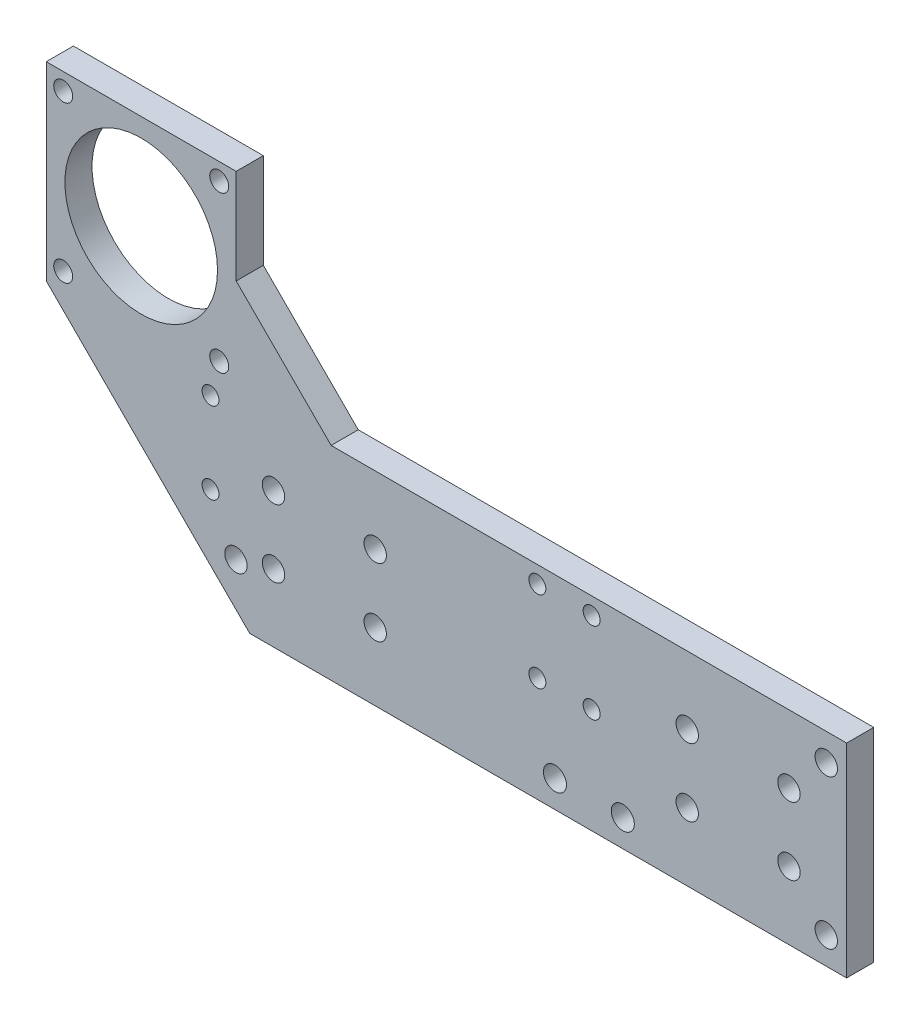
SolidWorks part; units mm, degrees
ref_plane "前视基准面" through (0, 0, 0) normal (0, 0, 1) x (1, 0, 0)
ref_plane "上视基准面" through (0, 0, 0) normal (0, 1, 0) x (1, 0, 0)
ref_plane "右视基准面" through (0, 0, 0) normal (1, 0, 0) x (0, 0, -1)
other "Configuration Table"
sketch "草图1" plane through (0, 0, 0) normal (0, 0, 1) x (1, 0, 0)
  line L1 (-56, -29) -> (56, -29)
  line L2 (-56, -29) -> (-56, 29)
  line L3 (-56, 29) -> (56, 29)
  line L4 (56, -29) -> (56, 29)
  line L5 (-56, -29) -> (56, 29) construction
  line L6 (-56, 29) -> (56, -29) construction
  point P0 (0, 0)
  dimension "D1" = 112
  dimension "D2" = 58
extrude "凸台-拉伸1" add sketch "草图1" along normal blind 4
sketch "草图2" plane through (0, 0, 4) normal (0, 0, 1) x (1, 0, 0)
  line L0 (56, 1) -> (-14, 1)
  line L1 (56, -29) -> (56, 29) construction
  line L3 (56, 29) -> (-56, 29) construction
  line L4 (-28, 29) -> (-56, 29)
  line L5 (-56, 29) -> (-56, 1)
  line L6 (-56, 29) -> (-56, -29) construction
  line L7 (-56, 1) -> (-26, -29)
  line L8 (-56, -29) -> (56, -29) construction
  line L9 (-26, -29) -> (56, -29)
  line L10 (56, -29) -> (56, 1)
  line L11 (-28, 29) -> (-28, 15)
  line L12 (-14, 1) -> (-28, 15)
  dimension "D1" = 45
extrude "切除-拉伸1" cut sketch "草图2" against normal blind 4 flip side to cut
sketch "草图3" plane through (0, 0, 4) normal (0, 0, 1) x (1, 0, 0)
  circle A0 centre (-42, 15) radius 11.25
  dimension "D1" = 22.5
extrude "切除-拉伸2" cut sketch "草图3" against normal blind 4
sketch "草图4" plane through (0, 0, 4) normal (0, 0, 1) x (1, 0, 0)
  circle A0 centre (-22.5, -19) radius 1.65
  circle A1 centre (-22.5, -9) radius 1.65
  circle A2 centre (-7.5, -19) radius 1.65
  circle A3 centre (-7.5, -9) radius 1.65
  circle A4 centre (38.5, -19) radius 1.65
  circle A5 centre (38.5, -9) radius 1.65
  circle A6 centre (53.5, -19) radius 1.65
  circle A7 centre (53.5, -9) radius 1.65
  circle A10 centre (19, -25) radius 1.7
  circle A11 centre (29, -25) radius 1.7
  dimension "D1" = 3.3
  dimension "D2" = 3.4
extrude "切除-拉伸3" cut sketch "草图4" against normal up to next
sketch "草图5" plane through (0, 0, 0) normal (0, 0, -1) x (-1, 0, 0)
  circle A0 centre (-16.406, -13.5) radius 1.25
  circle A1 centre (-24.406, -13.5) radius 1.25
  circle A2 centre (-16.406, -1.5) radius 1.25
  circle A3 centre (-24.406, -1.5) radius 1.25
  circle A4 centre (31.7799, -13.5) radius 1.25
  circle A5 centre (31.7799, -1.5) radius 1.25
  point P12 (-25.6794, -13.5)
  point P13 (-16.8753, -13.5)
  point P14 (-24.8754, -1.5)
  point P15 (-16.8753, -1.5)
  dimension "D1" = 2.5
extrude "切除-拉伸4" cut sketch "草图5" against normal up to next
sketch "草图6" plane through (56, 0, 0) normal (1, 0, 0) x (0, 0, -1)
  line L0 (0, -29) -> (0, 1) construction
  line L1 (0, -29) -> (-4, -29)
  line L2 (0, -29) -> (0, 1)
  line L3 (0, 1) -> (-4, 1)
  line L4 (-4, -29) -> (-4, 1)
  line L5 (-4, 1) -> (-4, 15) construction
sketch "草图8" plane through (0, 0, 0) normal (0, 0, -1) x (-1, 0, 0)
  line L0 (-56, -29) -> (-56, 1) construction
  line L1 (-56, 1) -> (-62, 1)
  line L2 (-56, 1) -> (-56, -29)
  line L3 (-56, -29) -> (-62, -29)
  line L4 (-62, 1) -> (-62, -29)
  dimension "D1" = 6
extrude "凸台-拉伸3" add sketch "草图8" against normal blind 4
sketch "草图10" plane through (0, 0, 4) normal (0, 0, 1) x (1, 0, 0)
  line L1 (62, 1) -> (62, -29) construction
  line L2 (-26, -29) -> (62, -29) construction
  line L3 (62, 1) -> (-14, 1) construction
  circle A0 centre (59, -25) radius 1.65
  circle A1 centre (59, -3) radius 1.65
  dimension "D1" = 3.3
  dimension "D2" = 3.3
  dimension "D3" = 3
  dimension "D4" = 3
  dimension "D5" = 4
  dimension "D6" = 4
extrude "切除-拉伸5" cut sketch "草图10" against normal up to next
sketch "草图11" plane through (0, 0, 4) normal (0, 0, 1) x (1, 0, 0)
  circle A0 centre (-28.0366, -20.5937) radius 1.65
  dimension "D1" = 3.3
extrude "切除-拉伸6" cut sketch "草图11" against normal up to next
sketch "草图13" plane through (0, 0, 0) normal (0, 0, -1) x (-1, 0, 0)
  line L1 (30.5, 26.5) -> (53.5, 26.5) construction
  line L2 (30.5, 26.5) -> (30.5, 3.5) construction
  line L3 (30.5, 3.5) -> (53.5, 3.5) construction
  line L4 (53.5, 26.5) -> (53.5, 3.5) construction
  line L5 (30.5, 26.5) -> (53.5, 3.5) construction
  line L6 (30.5, 3.5) -> (53.5, 26.5) construction
  circle A0 centre (53.5, 26.5) radius 1.4
  circle A1 centre (53.5, 3.5) radius 1.4
  circle A2 centre (30.5, 3.5) radius 1.4
  circle A3 centre (30.5, 26.5) radius 1.4
  point P0 (42, 15)
  dimension "D3" = 2.8
  dimension "D1" = 23
  dimension "D2" = 23
extrude "切除-拉伸7" cut sketch "草图13" against normal through all
